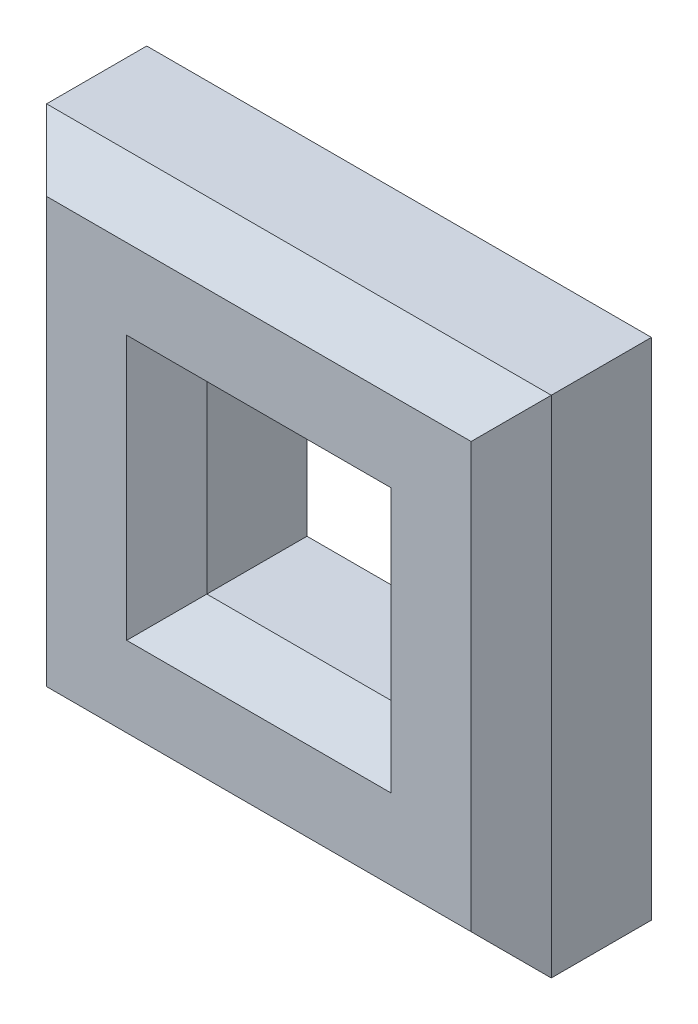
SolidWorks part; units mm, degrees
ref_plane "Front Plane" through (0, 0, 0) normal (0, 0, 1) x (1, 0, 0)
ref_plane "Top Plane" through (0, 0, 0) normal (0, 1, 0) x (1, 0, 0)
ref_plane "Right Plane" through (0, 0, 0) normal (1, 0, 0) x (0, 0, -1)
sketch "Sketch1" plane through (0, 0, 0) normal (0, 0, 1) x (1, 0, 0)
  line L1 (2.2981, -2.2981) -> (-2.2981, -2.2981)
  line L2 (2.2981, -2.2981) -> (2.2981, 2.2981)
  line L3 (2.2981, 2.2981) -> (-2.2981, 2.2981)
  line L4 (-2.2981, -2.2981) -> (-2.2981, 2.2981)
  line L5 (2.2981, -2.2981) -> (-2.2981, 2.2981) construction
  line L6 (2.2981, 2.2981) -> (-2.2981, -2.2981) construction
  line L7 (6.2981, -6.2981) -> (-6.2981, -6.2981)
  line L8 (6.2981, -6.2981) -> (6.2981, 6.2981)
  line L9 (6.2981, 6.2981) -> (-6.2981, 6.2981)
  line L10 (-6.2981, -6.2981) -> (-6.2981, 6.2981)
  line L11 (6.2981, -6.2981) -> (-6.2981, 6.2981) construction
  line L12 (6.2981, 6.2981) -> (-6.2981, -6.2981) construction
  circle A1 centre (0, 0) radius 3.25 construction
  point P0 (0, 0)
  point P7 (0, 0)
  dimension "D2" = 6.5
  dimension "D1" = 4
extrude "Boss-Extrude1" add sketch "Sketch1" along normal blind 3.5
chamfer "Chamfer1" distance 1 angle 45 8 edges at (2.2981, 0, 3.5) (0, 2.2981, 3.5) (-2.2981, 0, 3.5) (0, -2.2981, 3.5) (0, 6.2981, 3.5) (6.2981, 0, 3.5) (0, -6.2981, 3.5) (-6.2981, 0, 3.5)
